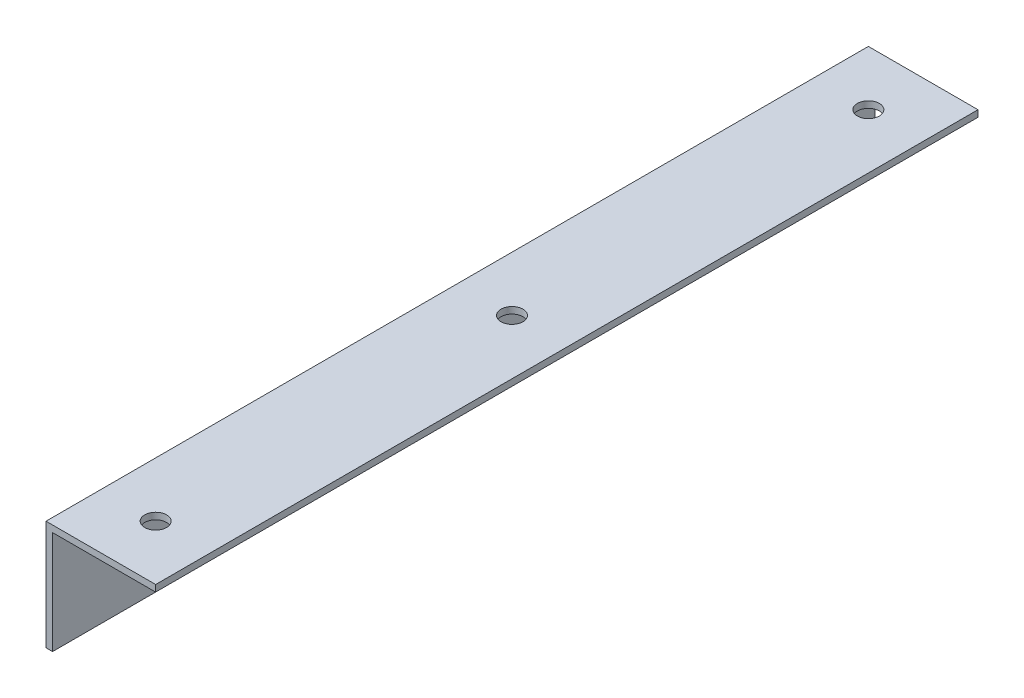
SolidWorks part; units mm, degrees
ref_plane "Front Plane" through (0, 0, 0) normal (0, 0, 1) x (1, 0, 0)
ref_plane "Top Plane" through (0, 0, 0) normal (0, 1, 0) x (1, 0, 0)
ref_plane "Right Plane" through (0, 0, 0) normal (1, 0, 0) x (0, 0, -1)
sketch "Sketch1" plane through (0, 0, 0) normal (0, 0, 1) x (1, 0, 0)
  line L0 (0, 0) -> (0, 20)
  line L1 (0, 20) -> (20, 20)
  line L2 (20, 20) -> (20, 18.8)
  line L3 (0, 0) -> (1.2, 0)
  line L4 (1.2, 0) -> (1.2, 18.8)
  line L5 (1.2, 18.8) -> (20, 18.8)
  dimension "D1" = 1.2
  dimension "D2" = 1.2
  dimension "D3" = 20
  dimension "D4" = 20
extrude "Boss-Extrude1" add sketch "Sketch1" along normal blind 150
sketch "Sketch2" plane through (0, 20, 0) normal (0, 1, 0) x (1, 0, 0)
  line L0 (10, 0) -> (10, -150) construction
  line L1 (20, 0) -> (0, 0) construction
  line L2 (20, -150) -> (0, -150) construction
  line L3 (0, -75) -> (20, -75) construction
  line L4 (0, -150) -> (0, 0) construction
  line L5 (20, -150) -> (20, 0) construction
  line L6 (0, -140) -> (20, -140) construction
  line L7 (0, -10) -> (20, -10) construction
  circle A0 centre (10, -75) radius 2
  circle A1 centre (10, -10) radius 2
  circle A2 centre (10, -140) radius 2
  dimension "D3" = 4
  dimension "D1" = 65
  dimension "D2" = 65
extrude "Cut-Extrude1" cut sketch "Sketch2" against normal blind 10
